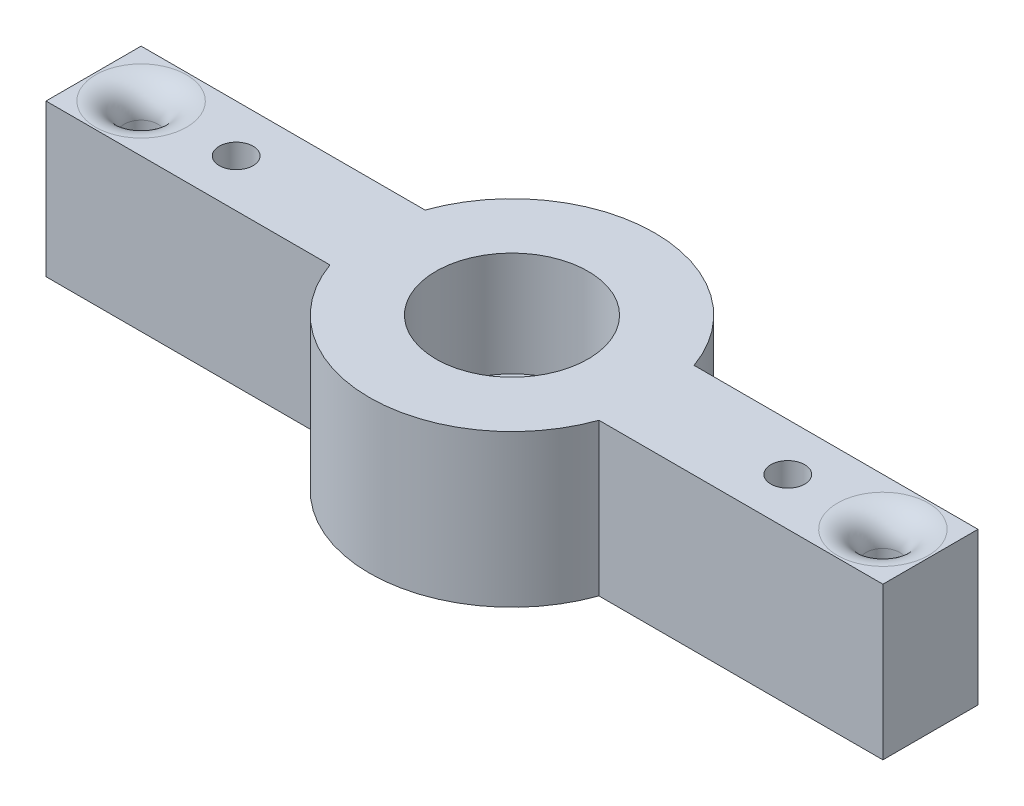
SolidWorks part; units mm, degrees
ref_plane "Front Plane" through (0, 0, 0) normal (0, 0, 1) x (1, 0, 0)
ref_plane "Top Plane" through (0, 0, 0) normal (0, 1, 0) x (1, 0, 0)
ref_plane "Right Plane" through (0, 0, 0) normal (1, 0, 0) x (0, 0, -1)
sketch "Sketch1" plane through (0, 0, 0) normal (0, 1, 0) x (1, 0, 0)
  line L0 (-7.0711, 2.5) -> (-22, 2.5)
  line L1 (-22, 2.5) -> (-22, -2.5)
  line L3 (-22, -2.5) -> (-7.0711, -2.5)
  line L4 (-26.3789, 0) -> (26.3789, 0) construction
  line L5 (-7.0711, 2.5) -> (-18.0711, 2.5) construction
  line L6 (7.0711, -2.5) -> (26.3789, -2.5) construction
  line L7 (0, 0) -> (0, 16.7972) construction
  line L8 (7.0711, 2.5) -> (22, 2.5)
  line L9 (22, 2.5) -> (22, -2.5)
  line L10 (22, -2.5) -> (7.0711, -2.5)
  arc A0 (-7.0711, -2.5) -> (7.0711, -2.5) centre (0, 0) ccw
  arc A1 (7.0711, 2.5) -> (-7.0711, 2.5) centre (0, 0) ccw
  circle A2 centre (-19.5, 0) radius 0.889
  circle A3 centre (0, 0) radius 1.875
  circle A4 centre (19.5, 0) radius 0.889
  circle A5 centre (-14.5, 0) radius 0.889
  circle A6 centre (14.5, 0) radius 0.889
  dimension "D3" = 15
  dimension "D5" = 3.75
extrude "Boss-Extrude1" add sketch "Sketch1" along normal blind 8
sketch "Sketch2" plane through (0, 8, 0) normal (0, 1, 0) x (1, 0, 0)
  circle A0 centre (0, 0) radius 4
  dimension "D1" = 8
extrude "Cut-Extrude1" cut sketch "Sketch2" against normal blind 5.5
fillet "Fillet1" radius 1.5 2 edges at (-19.5, 8, 0.889) (19.5, 8, 0.889)
